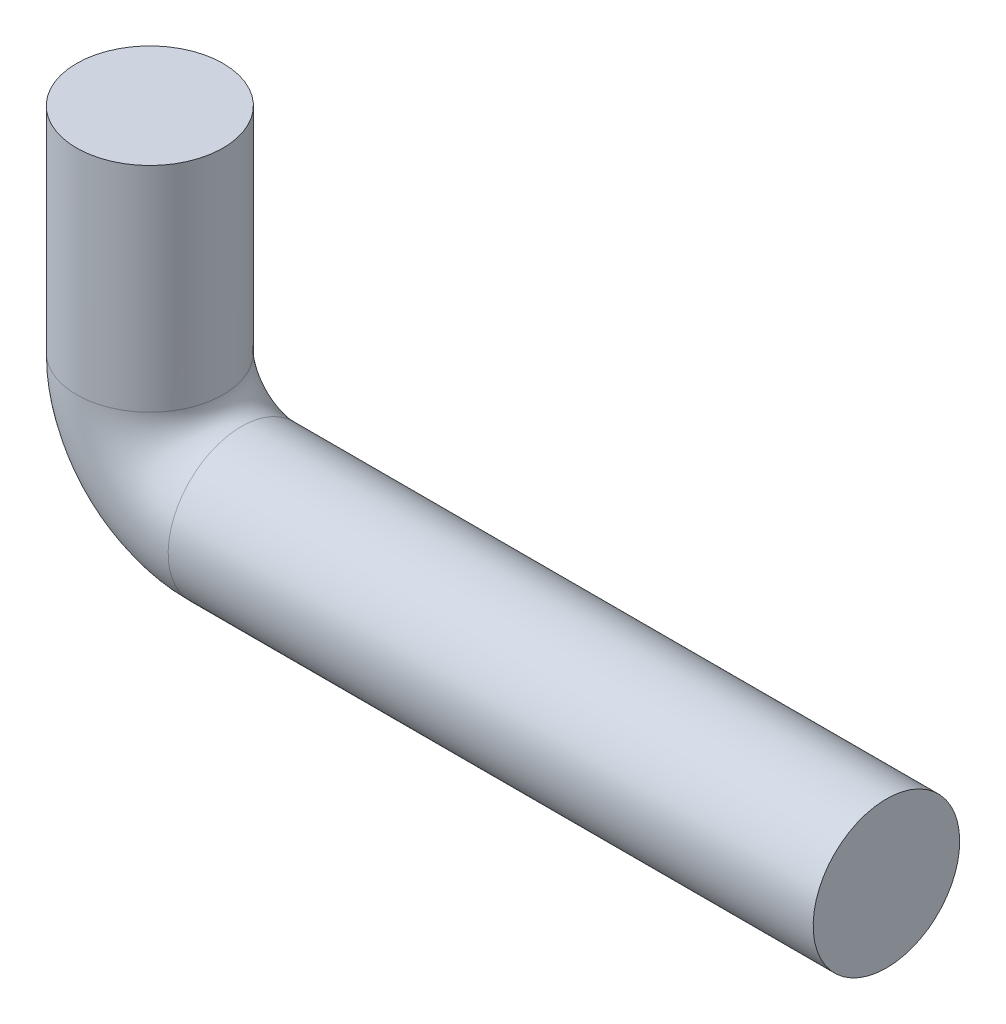
SolidWorks part; units mm, degrees
material "6061 Alloy"
ref_plane "Front Plane" through (0, 0, 0) normal (0, 0, 1) x (1, 0, 0)
ref_plane "Top Plane" through (0, 0, 0) normal (0, 1, 0) x (1, 0, 0)
ref_plane "Right Plane" through (0, 0, 0) normal (1, 0, 0) x (0, 0, -1)
sketch "Sketch path front shaft" plane through (0, 0, 0) normal (0, 0, 1) x (1, 0, 0)
  line L0 (15, 0) -> (120.65, 0)
  line L1 (0, 15) -> (0, 50)
  arc A0 (15, 0) -> (0, 15) centre (15, 15) cw
  point P6 (0, 0)
  dimension "D1" = 15
  dimension "D2" = 35
  dimension "D3" = 105.65
sweep "front shaft" add path "Sketch path front shaft" circular profile diameter 24 parameters "D3"=24
